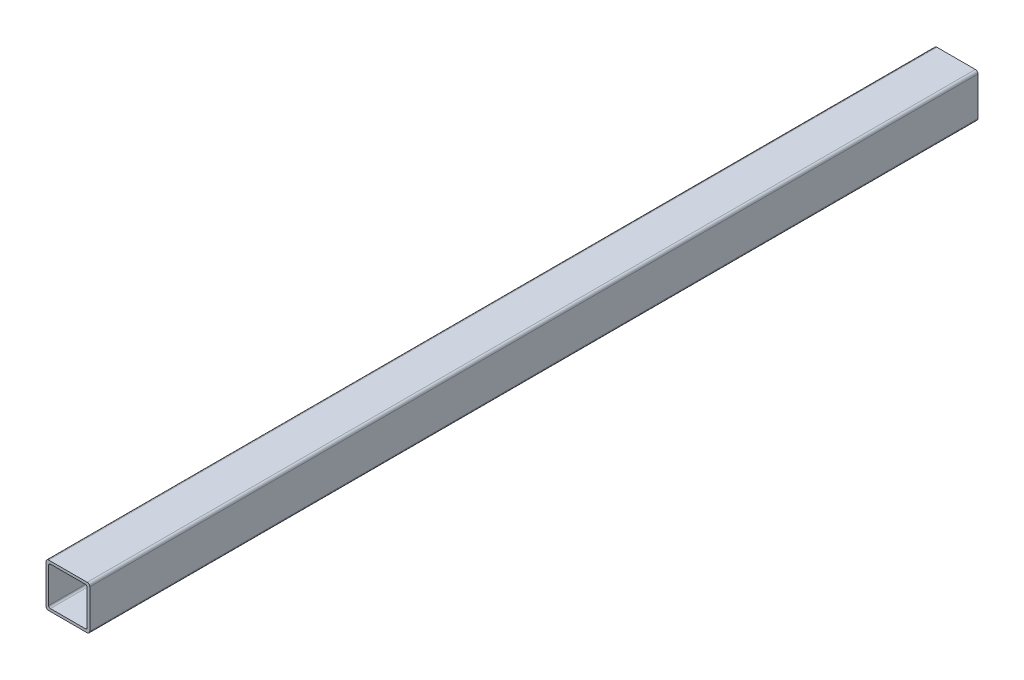
SolidWorks part; units mm, degrees
material "AISI 1020"
ref_plane "Спереди" through (0, 0, 0) normal (0, 0, 1) x (1, 0, 0)
ref_plane "Сверху" through (0, 0, 0) normal (0, 1, 0) x (1, 0, 0)
ref_plane "Справа" through (0, 0, 0) normal (1, 0, 0) x (0, 0, -1)
sketch "Эскиз1" plane through (0, 0, 0) normal (0, 0, 1) x (1, 0, 0)
  point P0 (0, 0)
  line B0 (-22, 25) -> (22, 25)
  line B1 (-25, 22) -> (-25, -22)
  line B2 (-22, -25) -> (22, -25)
  line B3 (25, 22) -> (25, -22)
  line B4 (-20, 22) -> (20, 22)
  line B5 (-22, 20) -> (-22, -20)
  line B6 (-20, -22) -> (20, -22)
  line B7 (22, 20) -> (22, -20)
  arc B8 (-25, -22) -> (-22, -25) centre (-22, -22) ccw
  arc B9 (22, -25) -> (25, -22) centre (22, -22) ccw
  arc B10 (22, 25) -> (25, 22) centre (22, 22) cw
  arc B11 (-22, 25) -> (-25, 22) centre (-22, 22) ccw
  arc B12 (-22, -20) -> (-20, -22) centre (-20, -20) ccw
  arc B13 (20, -22) -> (22, -20) centre (20, -20) ccw
  arc B14 (20, 22) -> (22, 20) centre (20, 20) cw
  arc B15 (-20, 22) -> (-22, 20) centre (-20, 20) ccw
sketch_block_instance "Труба профильная 50х50х3-1"
sketch_block "Труба профильная 50х50х3" parameters "D3"=3, "D4"=2, "D1"=50, "D2"=3
extrude "Бобышка-Вытянуть1" add sketch "Эскиз1" against normal up to surface (1015 mm away)
